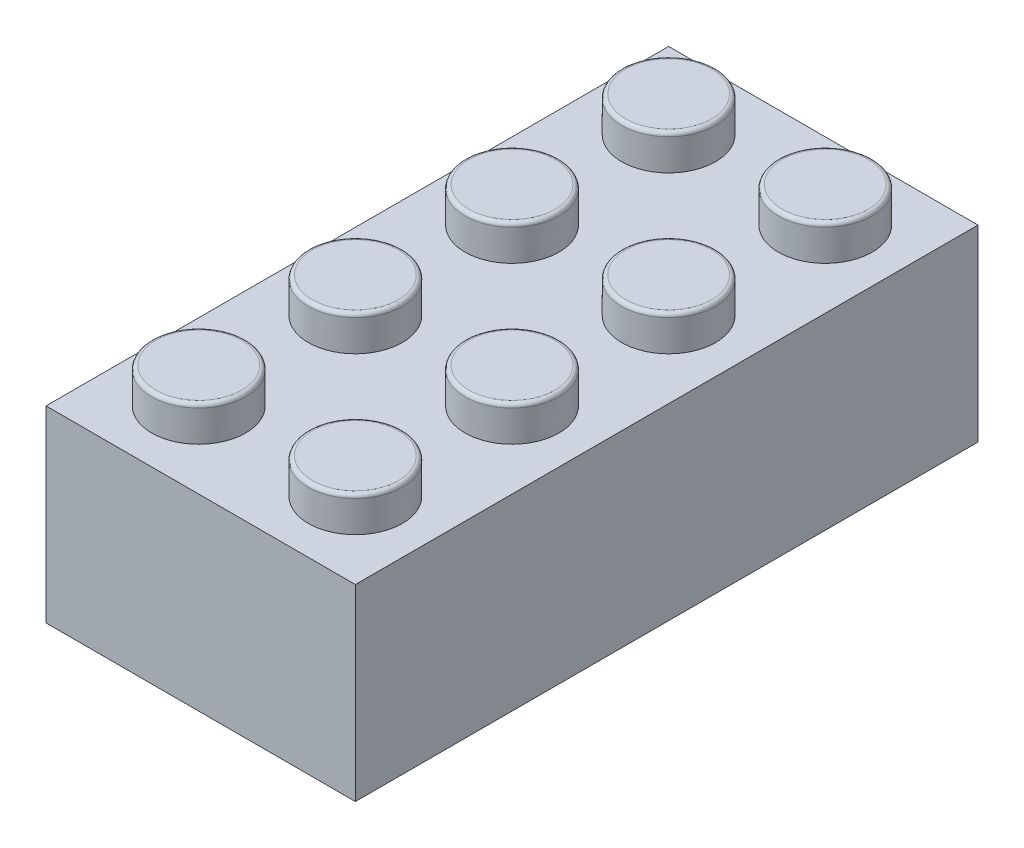
SolidWorks part; units mm, degrees
ref_plane "Front Plane" through (0, 0, 0) normal (0, 0, 1) x (1, 0, 0)
ref_plane "Top Plane" through (0, 0, 0) normal (0, 1, 0) x (1, 0, 0)
ref_plane "Right Plane" through (0, 0, 0) normal (1, 0, 0) x (0, 0, -1)
sketch "Sketch3" plane through (0, 0, 0) normal (0, 0, 1) x (1, 0, 0)
  line L1 (0, 0) -> (15.8, 0)
  line L2 (0, 0) -> (0, 9.6)
  line L3 (0, 9.6) -> (15.8, 9.6)
  line L4 (15.8, 0) -> (15.8, 9.6)
  dimension "D1" = 15.8
  dimension "D2" = 9.6
extrude "Boss-Extrude1" add sketch "Sketch3" along normal blind 31.8
sketch "Sketch5" plane through (0, 9.6, 0) normal (0, 1, 0) x (1, 0, 0)
  line L0 (15.8, 0) -> (0, 0) construction
  line L1 (0, -31.8) -> (0, 0) construction
  circle A0 centre (3.9, -3.9) radius 2.4
  circle A1 centre (11.9, -3.9) radius 2.4
  circle A2 centre (11.9, -11.9) radius 2.4
  circle A3 centre (11.9, -19.9) radius 2.4
  circle A4 centre (11.9, -27.9) radius 2.4
  circle A5 centre (3.9, -11.9) radius 2.4
  circle A6 centre (3.9, -19.9) radius 2.4
  circle A7 centre (3.9, -27.9) radius 2.4
  dimension "D1" = 4.8
  dimension "D2" = 3.9
  dimension "D3" = 3.9
  dimension "D4" = 2
  dimension "D5" = 4
extrude "Boss-Extrude2" add sketch "Sketch5" along normal blind 1.8
shell "Shell1" thickness 1
sketch "Sketch6" plane through (0, 8.6, 0) normal (0, -1, 0) x (-1, 0, 0)
  line L0 (0, -31.8) -> (0, 0) construction
  line L1 (0, -31.8) -> (-15.8, -31.8) construction
  circle A0 centre (-7.9, -23.9) radius 2.4
  circle A1 centre (-7.9, -23.9) radius 3.255
  circle A2 centre (-7.9, -15.9) radius 3.255
  circle A3 centre (-7.9, -15.9) radius 2.4
  circle A4 centre (-7.9, -7.9) radius 3.255
  circle A5 centre (-7.9, -7.9) radius 2.4
  dimension "D1" = 4.8
  dimension "D2" = 6.51
  dimension "D3" = 7.9
  dimension "D5" = 7.9
  dimension "D7" = 3
  dimension "D4" = 7.9
  dimension "D6" = 7.9
extrude "Boss-Extrude3" add sketch "Sketch6" along normal up to vertex (8.6 mm away)
sketch "Sketch8" plane through (0, 8.6, 0) normal (0, -1, 0) x (1, 0, 0)
  line L0 (0, 31.8) -> (15.8, 31.8) construction
  line L2 (1, 30.8) -> (1, 1) construction
  ellipse E0 centre (1, 27.9) end of major axis (1, 27.6) minor radius 0.2
  ellipse E1 centre (14.8, 27.9) end of major axis (14.8, 27.6) minor radius 0.2
  ellipse E2 centre (14.8, 19.9) end of major axis (14.8, 19.6) minor radius 0.2
  ellipse E3 centre (14.8, 11.9) end of major axis (14.8, 11.6) minor radius 0.2
  ellipse E4 centre (14.8, 3.9) end of major axis (14.8, 3.6) minor radius 0.2
  ellipse E5 centre (1, 19.9) end of major axis (1, 19.6) minor radius 0.2
  ellipse E6 centre (1, 11.9) end of major axis (1, 11.6) minor radius 0.2
  ellipse E7 centre (1, 3.9) end of major axis (1, 3.6) minor radius 0.2
  dimension "D2" = 0.2
  dimension "D1" = 3.9
  dimension "D3" = 2
  dimension "D4" = 4
extrude "Boss-Extrude4" add sketch "Sketch8" along normal up to vertex (8.6 mm away)
sketch "Sketch9" plane through (0, 8.6, 0) normal (0, -1, 0) x (1, 0, 0)
  line L0 (1, 30.8) -> (14.8, 30.8) construction
  line L1 (14.8, 30.8) -> (1, 30.8) construction
  line L2 (0, 31.8) -> (0, 0) construction
  ellipse E0 centre (3.9, 30.8) end of major axis (4.2, 30.8) minor radius 0.2
  ellipse E1 centre (11.9, 30.8) end of major axis (11.6, 30.8) minor radius 0.2
  ellipse E2 centre (11.9, 1) end of major axis (12.2, 1) minor radius 0.2
  ellipse E3 centre (3.9, 1) end of major axis (4.2, 1) minor radius 0.2
  dimension "D1" = 0.6
  dimension "D2" = 0.2
  dimension "D3" = 3.9
  dimension "D4" = 2
  dimension "D5" = 2
extrude "Boss-Extrude5" add sketch "Sketch9" along normal up to vertex (8.6 mm away)
sketch "Sketch10" plane through (0, 8.6, 0) normal (0, -1, 0) x (1, 0, 0)
  line L0 (1, 30.8) -> (1, 16.297)
  line L1 (1, 19.6) -> (1, 12.2) construction
  line L2 (10.9, 16.297) -> (10.9, 15.497)
  line L3 (1, 16.297) -> (4.9972, 16.297)
  line L4 (1, 16.297) -> (1, 15.497)
  line L5 (1, 15.497) -> (4.9972, 15.497)
  line L6 (4.9972, 16.297) -> (4.9972, 15.497)
  line L7 (10.9, 16.297) -> (14.8972, 16.297)
  line L8 (14.8972, 16.297) -> (14.8972, 15.497)
  line L9 (10.9, 15.497) -> (14.8972, 15.497)
  circle M2 centre (7.9, 15.9) radius 3.255
  line M21 (14.8, 12.2) -> (14.8, 19.6)
  line M35 (1, 19.6) -> (1, 12.2)
  dimension "D1" = 0.8
  dimension "D2" = 2
extrude "Boss-Extrude6" add sketch "Sketch10" along normal blind 6.3 contours L5 L3 M35 M2 | L9 L7 M2 M21
fillet "Fillet3" radius 0.2 8 edges at (3.9, 11.4, 30.3) (3.9, 11.4, 22.3) (3.9, 11.4, 14.3) (11.9, 11.4, 22.3) (11.9, 11.4, 14.3) (11.9, 11.4, 6.3) (3.9, 11.4, 6.3) (11.9, 11.4, 30.3)
